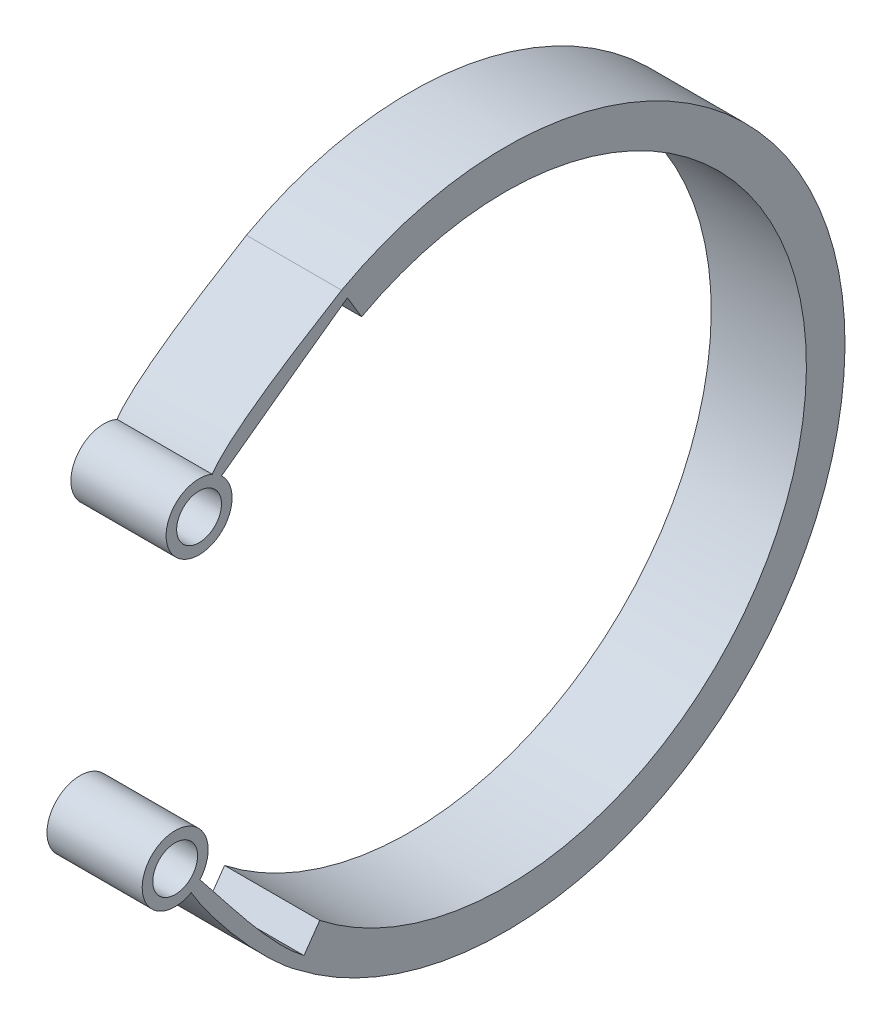
SolidWorks part; units mm, degrees
ref_plane "Front Plane" through (0, 0, 0) normal (0, 0, 1) x (1, 0, 0)
ref_plane "Top Plane" through (0, 0, 0) normal (0, 1, 0) x (1, 0, 0)
ref_plane "Right Plane" through (0, 0, 0) normal (1, 0, 0) x (0, 0, -1)
sketch "Sketch1" plane through (0, 0, 0) normal (1, 0, 0) x (0, 0, -1)
  line L0 (-35.1852, 24.3668) -> (-34.0694, 23.6365) construction
  line L1 (-17.2484, 31.7776) -> (-18.9614, 34.6005)
  line L2 (-24.1728, -31.1826) -> (-22.2763, -28.4796)
  line L3 (-37.708, -17.8771) -> (-36.669, -17.0412) construction
  arc A0 (-17.2484, 31.7776) -> (-22.2763, -28.4796) centre (0, 0) cw
  arc A1 (-34.0694, 23.6365) -> (-35.1852, 24.3668) centre (-36.7664, 20.7335) cw
  arc A2 (-19.6557, 35.7446) -> (-24.9419, -32.2788) centre (0, 0) cw
  circle A3 centre (-36.7664, 20.7335) radius 2.6924
  arc A4 (-37.708, -17.8771) -> (-36.669, -17.0412) centre (-39.637, -14.416) cw
  circle A5 centre (-39.637, -14.416) radius 2.6924
  spline S0 degree 2 poles (-18.9614, 34.6005) (-23.5806, 31.3331) (-34.0694, 23.6365) knots 0 0 0 1 1 1
  spline S1 degree 3 poles (-19.6557, 35.7446) (-24.4528, 32.8334) (-33.1068, 27.542) (-35.1852, 24.3668) knots 0 0 0 0 1 1 1 1
  spline S2 degree 3 poles (-24.9419, -32.2788) (-28.9, -29.5017) (-35.2858, -22.1004) (-37.708, -17.8771) knots 0 0 0 0 1 1 1 1
  spline S3 degree 3 poles (-24.1728, -31.1826) (-28.2478, -28.0912) (-32.8322, -21.81) (-36.669, -17.0412) knots 0 0 0 0 1 1 1 1
  dimension "D2" = 4.6355
  dimension "D3" = 40.7924
  dimension "D4" = 3.9624
  dimension "D5" = 26.3779
  dimension "D9" = 3.9624
  dimension "D10" = 26.7716
  dimension "D12" = 5.3848
  dimension "D13" = 5.3848
  dimension "D1" = 3.302
  dimension "D6" = 1.3335
  dimension "D7" = 3.302
  dimension "D8" = 65.9892
  dimension "D11" = 1.3335
extrude "Boss-Extrude1" add sketch "Sketch1" along normal blind 11.43
